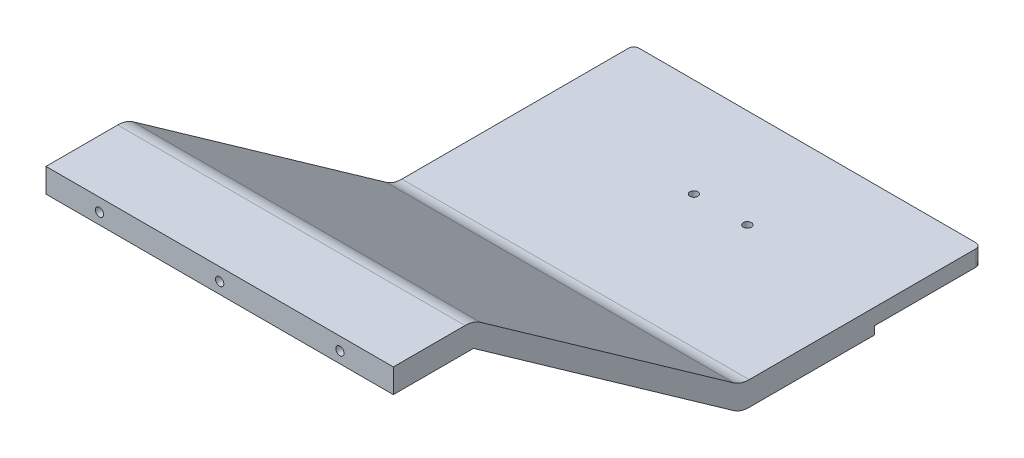
SolidWorks part; units mm, degrees
ref_plane "前视基准面" through (0, 0, 0) normal (0, 0, 1) x (1, 0, 0)
ref_plane "上视基准面" through (0, 0, 0) normal (0, 1, 0) x (1, 0, 0)
ref_plane "右视基准面" through (0, 0, 0) normal (1, 0, 0) x (0, 0, -1)
other "Configuration Table"
sketch "草图1" plane through (0, 0, 0) normal (0, 0, 1) x (1, 0, 0)
  line L0 (0, 0) -> (0, 79)
  line L1 (0, 79) -> (79, 79)
  line L2 (79, 79) -> (79, 70)
  line L3 (79, 70) -> (9, 70)
  line L4 (9, 70) -> (9, 0)
  line L5 (9, 0) -> (0, 0)
  dimension "D1" = 9
  dimension "D2" = 9
  dimension "D3" = 70
  dimension "D4" = 70
ref_plane "基准面1" through (0, 0, 100) normal (0, 0, 1) x (1, 0, 0)
sketch "草图2" plane through (0, 0, 100) normal (0, 0, 1) x (1, 0, 0)
  line L0 (0, 79) -> (-70.7107, 149.7107) construction
  line L1 (0, 0) -> (0, 79) construction
  line L2 (-70.7107, 149.7107) -> (-70.7107, 0)
  line L3 (-70.7107, 0) -> (-61.7107, 0)
  line L4 (-61.7107, 0) -> (-61.7107, 140.7107)
  line L5 (-61.7107, 140.7107) -> (79, 140.7107)
  line L6 (79, 140.7107) -> (79, 149.7107)
  line L7 (79, 149.7107) -> (-70.7107, 149.7107)
  line L8 (0, 0) -> (0, 79) construction
  line L9 (0, 79) -> (79, 79) construction
  dimension "D1" = 135
  dimension "D2" = 9
  dimension "D3" = 100
  dimension "D4" = 79
loft "放样1" add profiles "草图1", "草图2"
sketch "草图4" plane through (0, 0, 0) normal (0, 0, -1) x (-1, 0, 0)
  line L7 (-9, 0) -> (0, 0)
  line L8 (0, 0) -> (0, 79)
  line L9 (0, 79) -> (-79, 79)
  line L10 (-79, 79) -> (-79, 70)
  line L11 (-79, 70) -> (-77.7656, 70)
  line L12 (-77.7656, 70) -> (-9, 70)
  line L13 (-9, 70) -> (-9, 0)
  line L14 (-9, 0) -> (0, 0)
  line L15 (0, 0) -> (0, 79)
  line L16 (0, 79) -> (-79, 79)
  line L17 (-79, 79) -> (-79, 70)
  line L18 (-79, 70) -> (-77.7656, 70)
  line L19 (-77.7656, 70) -> (-9, 70)
  line L20 (-9, 70) -> (-9, 0)
  dimension "D1" = 0
extrude "凸台-拉伸1" add sketch "草图4" along normal blind 50
sketch "草图9" plane through (0, 0, -50) normal (0, 0, -1) x (-1, 0, 0)
  line L0 (-9, 70) -> (-9, 0) construction
  line L1 (-9, 70) -> (-55, 70)
  line L2 (-9, 70) -> (-9, 30)
  line L3 (-15, 64) -> (-55, 64)
  line L4 (-55, 70) -> (-55, 64)
  line L6 (-15, 64) -> (-15, 30)
  line L7 (-15, 30) -> (-9, 30)
  dimension "D1" = 6
  dimension "D2" = 46
  dimension "D3" = 6
  dimension "D4" = 40
extrude "凸台-拉伸3" add sketch "草图9" against normal blind 6
fillet "圆角1" radius 10 7 edges
sketch "草图11" plane through (0, 0, -44) normal (0, 0, 1) x (1, 0, 0)
  circle A0 centre (12, 45) radius 1.55
  circle A1 centre (12, 65) radius 1.55
  circle A2 centre (30, 67) radius 1.55
  circle A3 centre (50, 67) radius 1.55
  dimension "D1" = 3.1
extrude "切除-拉伸1" cut sketch "草图11" against normal through all
sketch "草图12" plane through (0, 0, -50) normal (0, 0, -1) x (-1, 0, 0)
  line L0 (0, 19) -> (0, 0)
  line L1 (0, 0) -> (0, 69) construction
  line L2 (0, 0) -> (-6, 0)
  line L3 (-9, 0) -> (0, 0) construction
  line L5 (-6, 0) -> (-6, 19)
  line L6 (0, 19) -> (-6, 19)
  line L7 (-2.9289, 76.0711) -> (-93.7798, -14.7798) construction
  line L8 (0, 0) -> (0, 69) construction
  line L9 (-60, 79) -> (-60, 73)
  line L10 (-79, 73) -> (-60, 73)
  line L11 (-79, 79) -> (-79, 73)
  line L12 (-60, 79) -> (-79, 79)
  arc A0 (0, 69) -> (-10, 79) centre (-10, 69) ccw construction
  dimension "D1" = 19
  dimension "D2" = 6
  dimension "D3" = 45
extrude "凸台-拉伸4" add sketch "草图12" along normal blind 40
fillet "圆角2" radius 2 9 edges at (3, 0, -90) (3, 19, -90) (9, 30, -47) (15, 30, -47) (15, 64, -47) (55, 70, -47) (55, 64, -47) (79, 76, -90) (60, 76, -90)
sketch "草图13" plane through (79, 0, 0) normal (1, 0, 0) x (0, 0, -1)
  line L0 (90, 79) -> (88, 79) construction
  line L1 (90, 79) -> (90, 73) construction
  line L9 (50, 73) -> (88, 73)
  line L10 (88, 73) -> (88, 79)
  line L11 (88, 79) -> (3.1784, 79)
  line L12 (-2.5951, 80.835) -> (-100, 149.7107)
  line L13 (-100, 149.7107) -> (-100, 149.2162)
  line L14 (-100, 149.2162) -> (-100, 140.7107)
  line L15 (-100, 140.7107) -> (-2.5951, 71.835)
  line L16 (3.1784, 70) -> (50, 70)
  line L17 (50, 70) -> (50, 73)
  line L18 (50, 73) -> (90, 73)
  line L19 (90, 73) -> (90, 79)
  line L20 (90, 79) -> (3.1784, 79)
  line L21 (-2.5951, 80.835) -> (-100, 149.7107)
  line L22 (-100, 149.7107) -> (-100, 149.2162)
  line L23 (-100, 149.2162) -> (-100, 140.7107)
  line L24 (-100, 140.7107) -> (-2.5951, 71.835)
  line L25 (3.1784, 70) -> (50, 70)
  line L26 (50, 70) -> (50, 73)
  arc A2 (-2.5951, 80.835) -> (3.1784, 79) centre (3.1784, 89) ccw
  arc A3 (-2.5951, 71.835) -> (3.1784, 70) centre (3.1784, 80) ccw
  arc A4 (-2.5951, 80.835) -> (3.1784, 79) centre (3.1784, 89) ccw
  arc A5 (-2.5951, 71.835) -> (3.1784, 70) centre (3.1784, 80) ccw
  dimension "D1" = 0
extrude "凸台-拉伸5" add sketch "草图13" along normal blind 130 separate body
delete or keep bodies "实体-删除/保留 1" type delete bodies bodies 112
sketch "草图14" plane through (0, 0, 100) normal (0, 0, 1) x (1, 0, 0)
  line L4 (79, 149.7107) -> (79, 140.7107)
  line L5 (79, 140.7107) -> (209, 140.7107)
  line L6 (209, 140.7107) -> (209, 149.7107)
  line L7 (209, 149.7107) -> (79, 149.7107)
  line L8 (79, 149.7107) -> (79, 140.7107)
  line L9 (79, 140.7107) -> (209, 140.7107)
  line L10 (209, 140.7107) -> (209, 149.7107)
  line L11 (209, 149.7107) -> (79, 149.7107)
  dimension "D1" = 0
extrude "凸台-拉伸6" add sketch "草图14" along normal blind 30
sketch "草图15" plane through (0, 0, 130) normal (0, 0, 1) x (1, 0, 0)
  line L0 (79, 149.7107) -> (79, 140.7107) construction
  line L1 (79, 140.7107) -> (209, 140.7107) construction
  circle A0 centre (99, 144.8907) radius 1.55
  circle A1 centre (144, 144.8907) radius 1.55
  circle A2 centre (189, 144.8907) radius 1.55
  dimension "D1" = 3.1
  dimension "D2" = 20
  dimension "D3" = 4.18
  dimension "D5" = 45
  dimension "D4" = 3
extrude "切除-拉伸2" cut sketch "草图15" against normal blind 5
fillet "圆角3" radius 2 2 edges at (79, 76, -90) (209, 76, -90)
sketch "草图16" plane through (0, 73, 0) normal (0, -1, 0) x (1, 0, 0)
  line L1 (144, 130) -> (144, 82.7932) construction
  line L2 (79, 130) -> (209, 130) construction
  line L3 (209, -50) -> (79, -50) construction
  circle A1 centre (158.5, -53) radius 1.5
  circle A2 centre (138.5, -53) radius 1.5
  dimension "D1" = 3
  dimension "D2" = 3
  dimension "D3" = 14.5
  dimension "D4" = 20
extrude "切除-拉伸3" cut sketch "草图16" against normal through all
fillet "圆角4" radius 10 1 edges at (144, 149.7107, 100)
